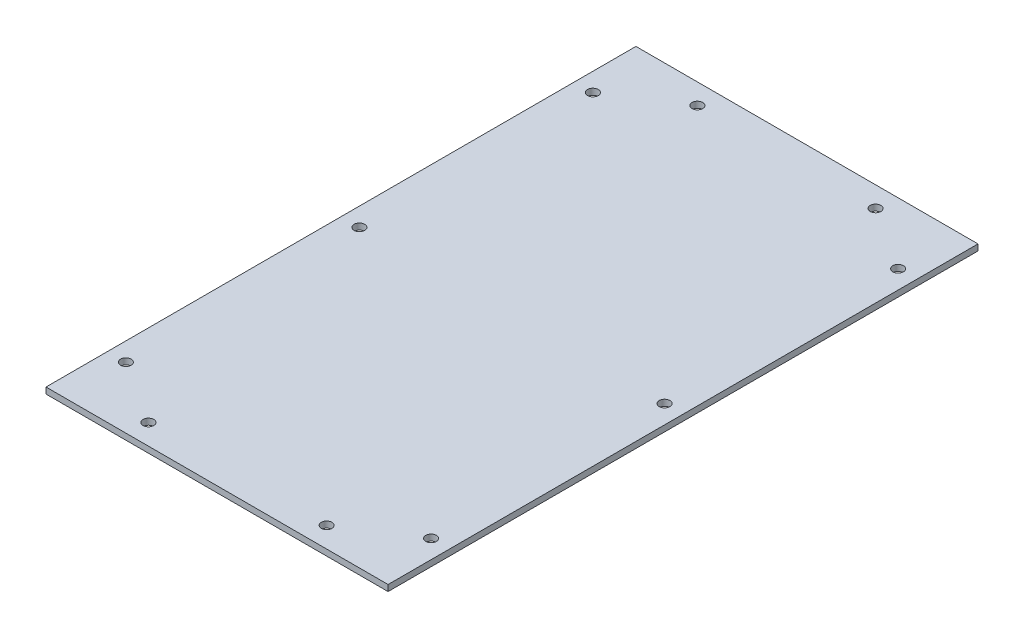
SolidWorks part; units mm, degrees
ref_plane "Alzado" through (0, 0, 0) normal (0, 0, 1) x (1, 0, 0)
ref_plane "Planta" through (0, 0, 0) normal (0, 1, 0) x (1, 0, 0)
ref_plane "Vista lateral" through (0, 0, 0) normal (1, 0, 0) x (0, 0, -1)
sketch "Croquis1" plane through (0, 0, 0) normal (0, 1, 0) x (1, 0, 0)
  line L0 (-74.5, 144) -> (-74.5, -144) construction
  line L1 (-83.5, 144) -> (83.5, 144)
  line L2 (-83.5, 144) -> (-83.5, -144)
  line L3 (-83.5, -144) -> (83.5, -144)
  line L4 (83.5, 144) -> (83.5, -144)
  line L5 (74.5, 144) -> (74.5, -144) construction
  line L6 (-83.5, 134) -> (83.5, 134) construction
  line L7 (-83.5, -134) -> (83.5, -134) construction
  circle A0 centre (-74.5, 114) radius 2.6
  circle A1 centre (-74.5, 0) radius 2.6
  circle A2 centre (-74.5, -114) radius 2.6
  circle A3 centre (74.5, 114) radius 2.6
  circle A5 centre (74.5, -114) radius 2.6
  circle A6 centre (74.5, 0) radius 2.6
  circle A7 centre (-43.5, 134) radius 2.6
  circle A8 centre (43.5, 134) radius 2.6
  circle A9 centre (-43.5, -134) radius 2.6
  circle A10 centre (43.5, -134) radius 2.6
  point P4 (0, 144)
  point P6 (-83.5, 0)
  dimension "D5" = 5.2
  dimension "D1" = 288
  dimension "D2" = 167
  dimension "D3" = 9
  dimension "D4" = 9
  dimension "D6" = 30
  dimension "D7" = 30
  dimension "D8" = 10
  dimension "D9" = 10
  dimension "D10" = 40
  dimension "D11" = 40
extrude "Saliente-Extruir1" add sketch "Croquis1" along normal blind 3
